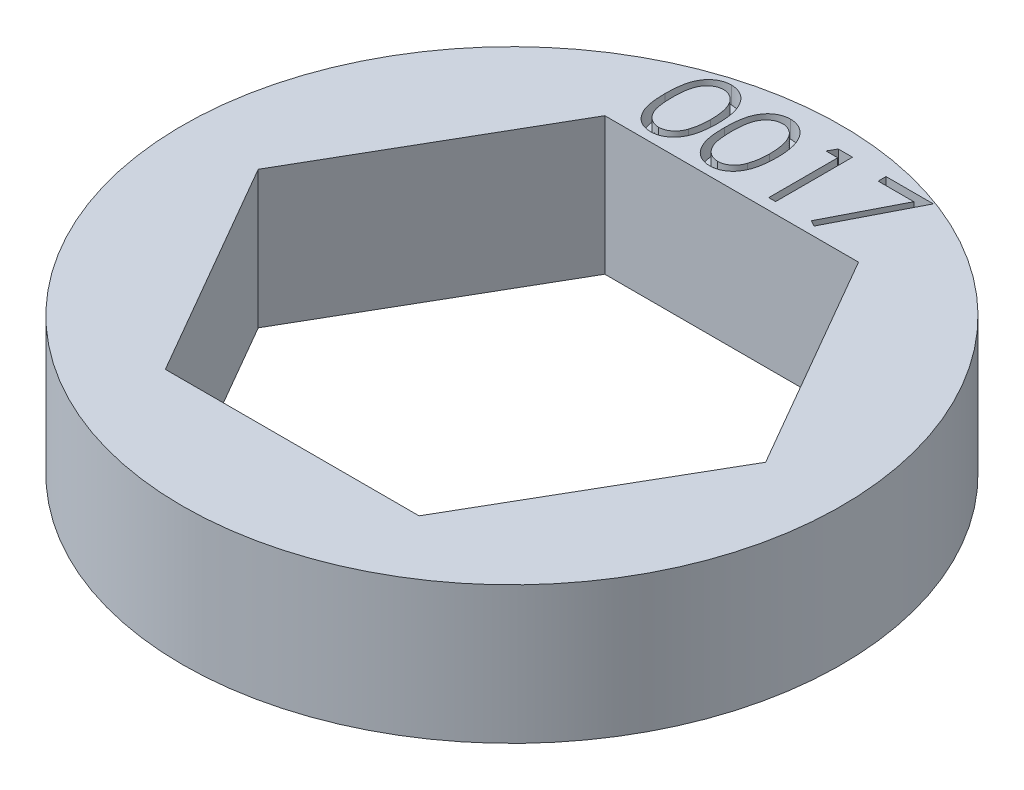
SolidWorks part; units mm, degrees
material "Nylon 101"
ref_plane "Front Plane" through (0, 0, 0) normal (0, 0, 1) x (1, 0, 0)
ref_plane "Top Plane" through (0, 0, 0) normal (0, 1, 0) x (1, 0, 0)
ref_plane "Right Plane" through (0, 0, 0) normal (1, 0, 0) x (0, 0, -1)
sketch "Sketch1" plane through (0, 0, 0) normal (0, 1, 0) x (1, 0, 0)
  line L1 (5.8659, 0) -> (2.9329, 5.08)
  line L2 (2.9329, 5.08) -> (-2.9329, 5.08)
  line L3 (-2.9329, 5.08) -> (-5.8659, 0)
  line L4 (-5.8659, 0) -> (-2.9329, -5.08)
  line L5 (-2.9329, -5.08) -> (2.9329, -5.08)
  line L6 (2.9329, -5.08) -> (5.8659, 0)
  circle A0 centre (0, 0) radius 7.62
  circle A1 centre (0, 0) radius 5.08 construction
  point P3 (0, 0)
  point P11 (0, 0)
  point P12 (0, 0)
  point P13 (0, 0)
  dimension "D1" = 15.24
  dimension "D2" = 10.16
extrude "Boss-Extrude1" add sketch "Sketch1" along normal blind 3.175
sketch "Sketch2" plane through (0, 3.175, 0) normal (0, 1, 0) x (1, 0, 0)
  line L0 (-2.748, 5.334) -> (2.8016, 5.334) construction
  line L1 (2.9329, 5.08) -> (-2.9329, 5.08) construction
  text T0 "0017" font "Century Gothic" height 1.778
  point P5 (-2.5135, 5.334)
  point P6 (-2.748, 5.334)
  dimension "D1" = 0.254
extrude "Cut-Extrude1" cut sketch "Sketch2" against normal blind 0.4
